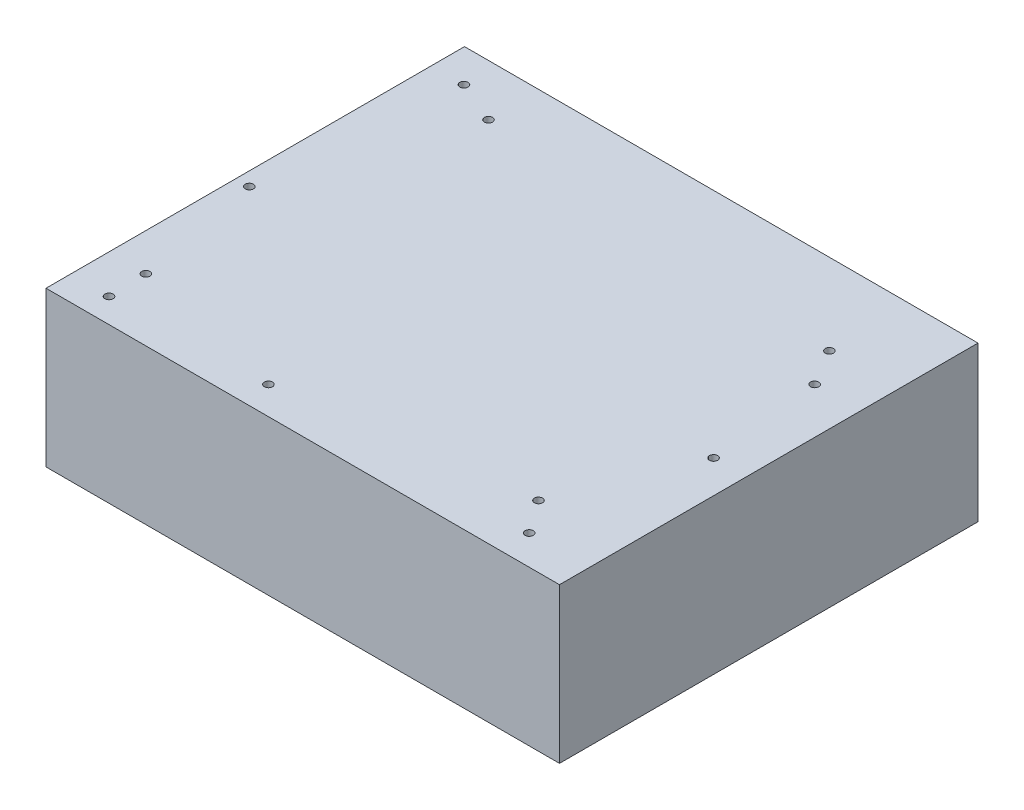
SolidWorks part; units mm, degrees
material "6061-T6 (SS)"
ref_plane "Front Plane" through (0, 0, 0) normal (0, 0, 1) x (1, 0, 0)
ref_plane "Top Plane" through (0, 0, 0) normal (0, 1, 0) x (1, 0, 0)
ref_plane "Right Plane" through (0, 0, 0) normal (1, 0, 0) x (0, 0, -1)
sketch "Sketch1" plane through (0, 0, 0) normal (0, 1, 0) x (1, 0, 0)
  line L0 (-187.5, 150) -> (-187.5, 170)
  line L2 (187.5, 152.7698) -> (187.5, -135.6424)
  line L4 (-187.5, 150) -> (-187.5, -135.6424)
  line L7 (-187.5, 170) -> (187.5, 170)
  line L8 (187.5, 170) -> (187.5, 152.7698)
  line L10 (-187.5, -135.6424) -> (187.5, -135.6424)
  point P0 (0, 0)
extrude "Boss-Extrude1" add sketch "Sketch1" along normal blind 113.03
sketch "A-ARM SKETCHES" plane through (0, 113.03, 0) normal (0, 1, 0) x (1, 0, 0)
  circle A0 centre (-163.6091, 145.6958) radius 3
  circle A1 centre (-132.4558, 132.4676) radius 3
  circle A2 centre (138.154, 110.8204) radius 3
  circle A3 centre (154.0092, 84.2079) radius 3
  circle A4 centre (163.6037, 0.7881) radius 3
  circle A5 centre (126.547, -90.0364) radius 3
  circle A6 centre (143.7538, -114.0298) radius 3
  circle A7 centre (-177.5488, 2.9148) radius 3
  circle A8 centre (-160.1589, -90.0364) radius 3
  circle A9 centre (-159.3225, -117.8223) radius 3
  circle A10 centre (-45.4504, -115.2517) radius 3
  line B0 (-177.5488, 2.9148) -> (143.7538, -114.0298) construction
  line B1 (-177.5488, 2.9148) -> (138.154, 110.8204) construction
  line B2 (-160.1589, -90.0364) -> (126.547, -90.0364) construction
  line B3 (-160.1589, -90.0364) -> (-2.8379, 93.9638) construction
  line B4 (163.6037, 0.7881) -> (-159.3225, -117.8223) construction
  line B5 (163.6037, 0.7881) -> (-163.6091, 145.6958) construction
  line B6 (154.0092, 84.2079) -> (-45.4504, -115.2517) construction
  line B7 (154.0092, 84.2079) -> (-132.4558, 132.4676) construction
sketch_block_instance "REAR LOWER-1"
sketch_block "REAR LOWER" parameters "D1"=38.87, "D2"=341.9231, "D3"=333.6344
sketch_block_instance "REAR UPPER-1"
sketch_block "REAR UPPER" parameters "D1"=49.469, "D2"=286.7059, "D3"=242.0867
sketch_block_instance "FRONT LOWER-1"
sketch_block "FRONT LOWER" parameters "D1"=44.055, "D2"=357.8638, "D3"=344.02
sketch_block_instance "FRONT UPPER-1"
sketch_block "FRONT UPPER" parameters "D1"=54.563, "D2"=282.0785, "D3"=290.5017
extrude "A-ARM HOLES" cut sketch "A-ARM SKETCHES" against normal blind 20 contours A0 | A1 | A7 | A8 | A9 | A10 | A6 | A5 | A4 | A3 | A2
sketch "ALUMINUM BLOCK" plane through (0, 113.03, 0) normal (0, 1, 0) x (1, 0, 0)
  line L0 (-187.5, -135.6424) -> (-187.5, 207.2576) construction
  line L1 (-187.5, 207.2576) -> (-85.9, 207.2576) construction
  line L2 (-85.9, 207.2576) -> (-85.9, 137.4076) construction
  line L3 (-85.9, 137.4076) -> (98.25, 137.4076) construction
  line L4 (-187.5, -135.6424) -> (244.3, -135.6424) construction
  line L5 (244.3, -135.6424) -> (244.3, -46.7424) construction
  line L6 (244.3, -46.7424) -> (98.25, 137.4076) construction
